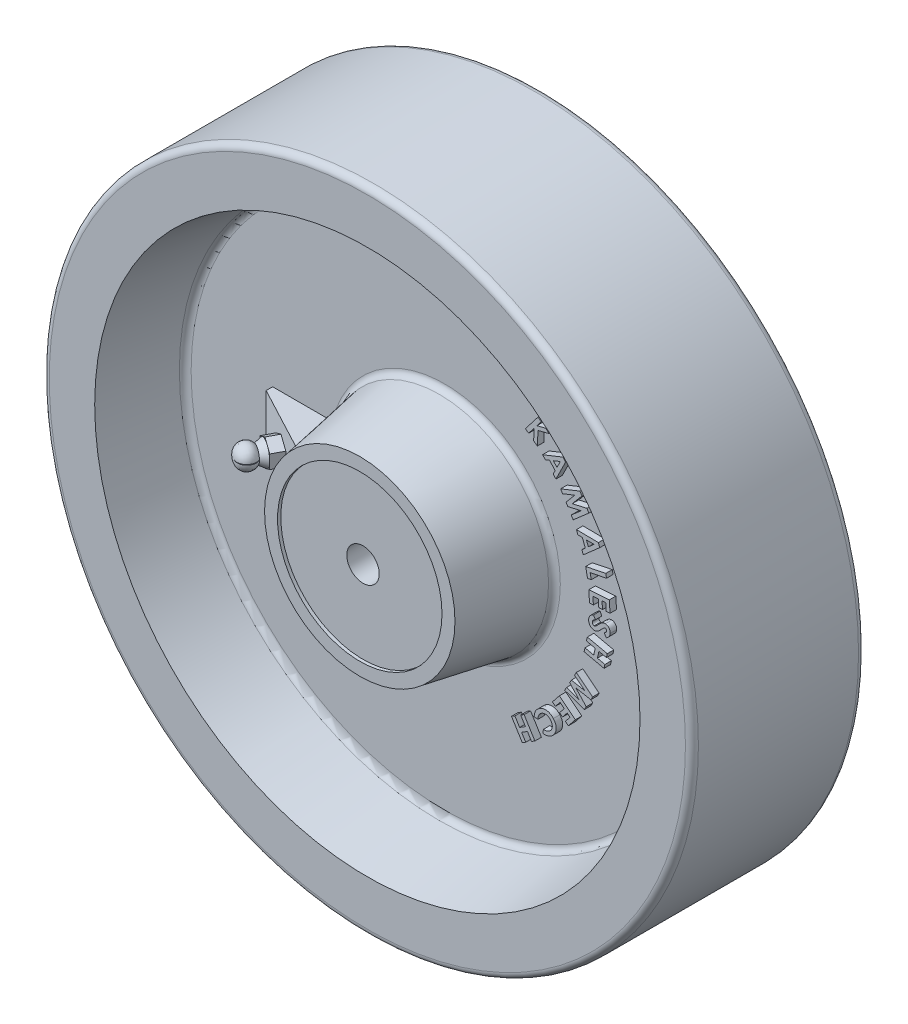
SolidWorks part; units mm, degrees
ref_plane "Front Plane" through (0, 0, 0) normal (0, 0, 1) x (1, 0, 0)
ref_plane "Top Plane" through (0, 0, 0) normal (0, 1, 0) x (1, 0, 0)
ref_plane "Right Plane" through (0, 0, 0) normal (1, 0, 0) x (0, 0, -1)
sketch "Sketch1" plane through (0, 0, 0) normal (0, 0, 1) x (1, 0, 0)
  circle A0 centre (0, 0) radius 150
  circle A1 centre (0, 0) radius 138
  dimension "D1" = 300
  dimension "D2" = 12
extrude "Boss-Extrude1" add sketch "Sketch1" along normal blind 80
fillet "Fillet1" radius 3 2 edges at (150, 0, 0) (150, 0, 80)
sketch "Sketch2" plane through (0, 0, 0) normal (0, 1, 0) x (1, 0, 0)
  line L0 (-150, -40) -> (0, -40) construction
  line L1 (0, -132.4611) -> (0, 52.4611) construction
  line L2 (-150, -3) -> (-150, -77) construction
  line L3 (0, 2) -> (0, -82)
  line L4 (0, -82) -> (-38, -82)
  line L5 (-38, -82) -> (-38, -83.5)
  line L6 (-38, -83.5) -> (-44, -83.5)
  line L7 (-44, -83.5) -> (-50.9208, -44.25)
  line L8 (-50.9208, -44.25) -> (-119.6963, -44.25)
  line L9 (-119.6963, -44.25) -> (-126, -80)
  line L10 (-126, -80) -> (-138, -80)
  line L11 (-138, -80) -> (-138, 0)
  line L12 (-126, 0) -> (-138, 0)
  line L13 (-119.6963, -35.75) -> (-126, 0)
  line L14 (-50.9208, -35.75) -> (-119.6963, -35.75)
  line L15 (-44, 3.5) -> (-50.9208, -35.75)
  line L16 (-38, 3.5) -> (-44, 3.5)
  line L17 (-38, 2) -> (-38, 3.5)
  line L18 (0, 2) -> (-38, 2)
  point P18 (-138, -40)
  dimension "D1" = 42
  dimension "D2" = 40
  dimension "D3" = 138
  dimension "D4" = 12
  dimension "D5" = 100
  dimension "D6" = 6
  dimension "D7" = 1.5
  dimension "D8" = 38
  dimension "D9" = 100
  dimension "D10" = 8.5
revolve "Revolve1" add sketch "Sketch2" angle 360 about L1
sketch "Sketch4" plane through (0, 0, 0) normal (0, 1, 0) x (1, 0, 0)
  line L0 (-44.5266, -64.25) -> (-44.5266, -44.25)
  line L1 (-50.9208, -44.25) -> (50.9208, -44.25) construction
  line L2 (-44.5266, -44.25) -> (-79.5266, -44.25)
  line L3 (-119.6963, -44.25) -> (119.6963, -44.25) construction
  line L4 (-79.5266, -44.25) -> (-79.5266, -47.25)
  line L5 (-79.5266, -47.25) -> (-47.5266, -64.25)
  line L7 (-47.5266, -64.25) -> (-44.5266, -64.25)
  dimension "D1" = 3
  dimension "D2" = 3
  dimension "D3" = 35
  dimension "D4" = 20
extrude "Boss-Extrude2" add sketch "Sketch4" along normal mid plane 25
sketch "Sketch5" plane through (-37.0809, 0, 69.7993) normal (-0.4692, 0, 0.8831) x (0.8831, 0, 0.4692)
  line L1 (-31.4622, -6.2574) -> (-26.0432, -3.1287)
  line L2 (-26.0432, -3.1287) -> (-26.0432, 3.1287)
  line L3 (-26.0432, 3.1287) -> (-31.4622, 6.2574)
  line L4 (-31.4622, 6.2574) -> (-36.8813, 3.1287)
  line L5 (-36.8813, 3.1287) -> (-36.8813, -3.1287)
  line L6 (-36.8813, -3.1287) -> (-31.4622, -6.2574)
  circle A0 centre (-31.4622, 0) radius 5.419 construction
extrude "Boss-Extrude3" add sketch "Sketch5" along normal blind 5.5
sketch "Sketch6" plane through (-39.6612, 0, 74.6564) normal (-0.4692, 0, 0.8831) x (0.8831, 0, 0.4692)
  circle A0 centre (-31.4622, 0) radius 5.419
extrude "Boss-Extrude4" add sketch "Sketch6" along normal blind 3 draft 30
sketch "Sketch7" plane through (0, 0, 0) normal (0, 1, 0) x (1, 0, 0)
  line L0 (-67.446, -59.8958) -> (-77.633, -78.9571) construction
  line L1 (-72.5395, -69.4264) -> (-68.8713, -62.5626)
  line L2 (-68.8713, -62.5626) -> (-65.5975, -64.2749)
  arc A0 (-72.5395, -69.4264) -> (-65.5975, -64.2749) centre (-69.7331, -65.955) ccw
revolve "Revolve10" add sketch "Sketch7" angle 197 about L1
sketch "Sketch8" plane through (-2.3561, -8.7381, -1.2592) normal (0.2579, 0.9563, 0.1378) x (0.9662, -0.2552, -0.0368)
  line L5 (-70.6733, -60.8787) -> (-72.0482, -60.1146)
  line L6 (-72.0482, -60.1146) -> (-72.0485, -60.094)
  line L7 (-72.0485, -60.094) -> (-72.0521, -60.0919)
  line L8 (-72.6399, -68.7166) -> (-68.8432, -61.923)
  line L9 (-68.8432, -61.923) -> (-70.6733, -60.8787)
  line L10 (-70.6733, -60.8787) -> (-72.0482, -60.1146)
  line L11 (-72.0482, -60.1146) -> (-72.0485, -60.094)
  line L12 (-72.0485, -60.094) -> (-72.0521, -60.0919)
  line L13 (-72.6399, -68.7166) -> (-68.8432, -61.923)
  line L14 (-68.8432, -61.923) -> (-70.6733, -60.8787)
  arc A1 (-72.0521, -60.0919) -> (-72.6399, -68.7166) centre (-71.2333, -64.4801) ccw
  arc A2 (-72.0521, -60.0919) -> (-72.6399, -68.7166) centre (-71.2333, -64.4801) ccw
  dimension "D1" = 0
revolve "Revolve16" add sketch "Sketch8" angle 160 about L13
fillet "Fillet2" radius 3 4 edges at (50.9208, 0, 35.75) (119.6963, 0, 35.75) (50.9208, 0, 44.25) (119.6963, 0, 44.25)
sketch "Sketch9" plane through (0, 0, 82) normal (0, 0, 1) x (1, 0, 0)
  circle A0 centre (0, 0) radius 7.5
  dimension "D1" = 15
extrude "Cut-Extrude1" cut sketch "Sketch9" against normal blind 200
sketch "Sketch10" plane through (0, 0, 44.25) normal (0, 0, 1) x (1, 0, 0)
  arc A0 (39.4479, 57.8262) -> (33.0266, -61.7191) centre (0, 0) cw construction
  text T0 "KAMALESH MECH" font "Century Gothic" height in points 36
  dimension "D1" = 70
extrude "Boss-Extrude5" add sketch "Sketch10" along normal blind 3
scale "Scale1" scale about centroid uniform scaling yes scale factor 0.25
